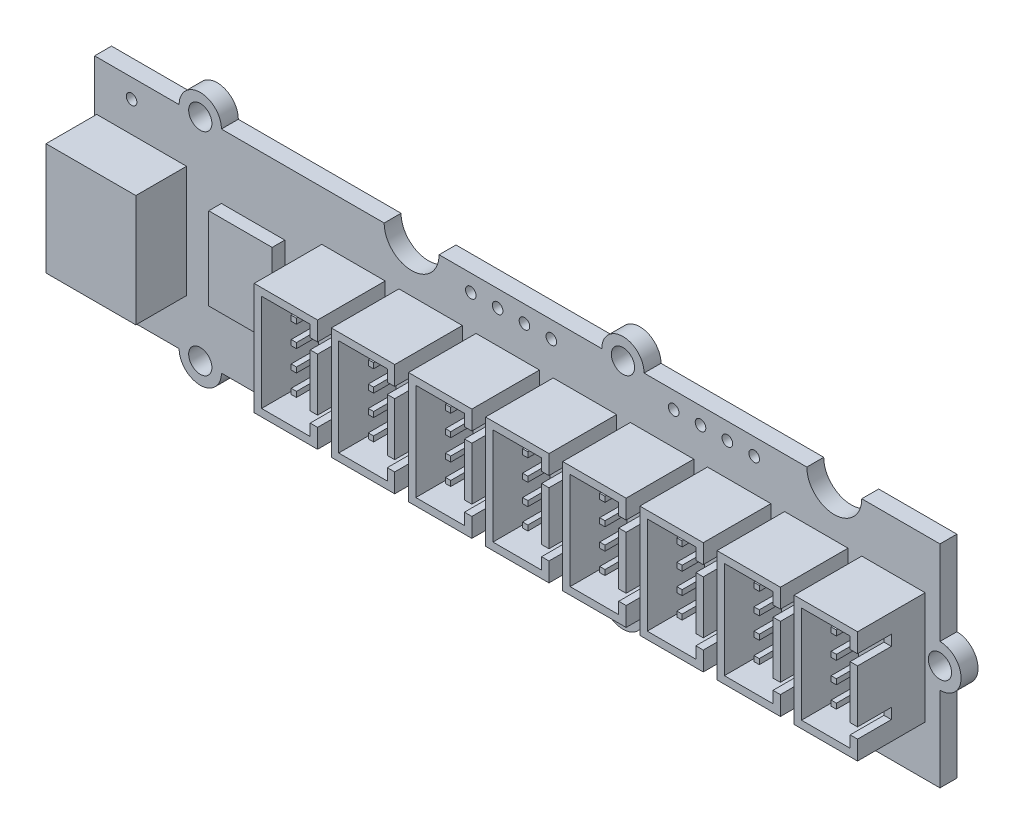
SolidWorks part; units mm, degrees
other "Grove_2"
other "Grove_1"
other "Grove_9"
other "Grove_8"
other "Grove_7"
other "Grove_6"
other "Grove_4"
other "PCB_estime"
other "Grove_3"
other "TCA9548A"
other "Grove_5"
ref_plane "Plan de face" through (0, 0, 0) normal (0, 0, 1) x (1, 0, 0)
ref_plane "Plan de dessus" through (0, 0, 0) normal (0, 1, 0) x (1, 0, 0)
ref_plane "Plan de droite" through (0, 0, 0) normal (1, 0, 0) x (0, 0, -1)
sketch "Esquisse1" plane through (0, 0, 0) normal (0, 0, 1) x (1, 0, 0)
  line L1 (0, 0) -> (80, 0)
  line L2 (0, 0) -> (0, 20)
  line L3 (0, 20) -> (80, 20)
  line L4 (80, 0) -> (80, 20)
extrude "PCB_80x20_epaisseur_ESTIMEE_1_6" add sketch "Esquisse1" along normal blind 1.6 separate body
sketch "Esquisse2" plane through (0, 0, 0) normal (0, 0, 1) x (1, 0, 0)
  circle A0 centre (10, 0) radius 2
  circle A1 centre (10, 20) radius 2
  circle A2 centre (50, 0) radius 2
  circle A3 centre (50, 20) radius 2
  circle A4 centre (80, 10) radius 2
extrude "Oreilles_fixation_ESTIMEES" add sketch "Esquisse2" along normal blind 1.6
sketch "Esquisse3" plane through (0, 0, 0) normal (0, 0, 1) x (1, 0, 0)
  circle A0 centre (10, 0) radius 1.1
  circle A1 centre (10, 20) radius 1.1
  circle A2 centre (50, 0) radius 1.1
  circle A3 centre (50, 20) radius 1.1
  circle A4 centre (80, 10) radius 1.1
  circle A5 centre (30, 0) radius 2.6
  circle A6 centre (30, 20) radius 2.6
  circle A7 centre (70, 0) radius 2.6
  circle A8 centre (70, 20) radius 2.6
  circle A9 centre (0, 10) radius 2.6
extrude "Percages_D2_2_et_encoches_ESTIMES" cut sketch "Esquisse3" against normal blind 2 from offset 1.6
sketch "Esquisse4" plane through (0, 0, 0) normal (0, 0, 1) x (1, 0, 0)
  circle A0 centre (35.6, 1.6) radius 0.5
  circle A1 centre (35.6, 18.4) radius 0.5
  circle A2 centre (38.14, 1.6) radius 0.5
  circle A3 centre (38.14, 18.4) radius 0.5
  circle A4 centre (40.68, 1.6) radius 0.5
  circle A5 centre (40.68, 18.4) radius 0.5
  circle A6 centre (43.22, 1.6) radius 0.5
  circle A7 centre (43.22, 18.4) radius 0.5
  circle A8 centre (54.8, 1.6) radius 0.5
  circle A9 centre (54.8, 18.4) radius 0.5
  circle A10 centre (57.34, 1.6) radius 0.5
  circle A11 centre (57.34, 18.4) radius 0.5
  circle A12 centre (59.88, 1.6) radius 0.5
  circle A13 centre (59.88, 18.4) radius 0.5
  circle A14 centre (62.42, 1.6) radius 0.5
  circle A15 centre (62.42, 18.4) radius 0.5
  circle A16 centre (3.5, 18.2) radius 0.5
extrude "Trous_auxiliaires_ESTIMES" cut sketch "Esquisse4" against normal blind 2 from offset 1.6
sketch "Esquisse5" plane through (0, 0, 0) normal (0, 0, 1) x (1, 0, 0)
  line L1 (21.5, 4.7) -> (27.5, 4.7)
  line L2 (21.5, 4.7) -> (21.5, 15.3)
  line L3 (21.5, 15.3) -> (27.5, 15.3)
  line L4 (27.5, 4.7) -> (27.5, 15.3)
  line L6 (28.8, 4.7) -> (34.8, 4.7)
  line L7 (28.8, 4.7) -> (28.8, 15.3)
  line L8 (28.8, 15.3) -> (34.8, 15.3)
  line L9 (34.8, 4.7) -> (34.8, 15.3)
  line L11 (36.1, 4.7) -> (42.1, 4.7)
  line L12 (36.1, 4.7) -> (36.1, 15.3)
  line L13 (36.1, 15.3) -> (42.1, 15.3)
  line L14 (42.1, 4.7) -> (42.1, 15.3)
  line L16 (43.4, 4.7) -> (49.4, 4.7)
  line L17 (43.4, 4.7) -> (43.4, 15.3)
  line L18 (43.4, 15.3) -> (49.4, 15.3)
  line L19 (49.4, 4.7) -> (49.4, 15.3)
  line L21 (50.7, 4.7) -> (56.7, 4.7)
  line L22 (50.7, 4.7) -> (50.7, 15.3)
  line L23 (50.7, 15.3) -> (56.7, 15.3)
  line L24 (56.7, 4.7) -> (56.7, 15.3)
  line L26 (58, 4.7) -> (64, 4.7)
  line L27 (58, 4.7) -> (58, 15.3)
  line L28 (58, 15.3) -> (64, 15.3)
  line L29 (64, 4.7) -> (64, 15.3)
  line L31 (65.3, 4.7) -> (71.3, 4.7)
  line L32 (65.3, 4.7) -> (65.3, 15.3)
  line L33 (65.3, 15.3) -> (71.3, 15.3)
  line L34 (71.3, 4.7) -> (71.3, 15.3)
  line L36 (72.6, 4.7) -> (78.6, 4.7)
  line L37 (72.6, 4.7) -> (72.6, 15.3)
  line L38 (72.6, 15.3) -> (78.6, 15.3)
  line L39 (78.6, 4.7) -> (78.6, 15.3)
extrude "Huit_connecteurs_sorties_ESTIMES" add sketch "Esquisse5" along normal blind 6.4 from offset 1.6 separate body
sketch "Esquisse6" plane through (0, 0, 0) normal (0, 0, 1) x (1, 0, 0)
  line L1 (22.2, 5.4) -> (26.8, 5.4)
  line L2 (22.2, 5.4) -> (22.2, 14.6)
  line L3 (22.2, 14.6) -> (26.8, 14.6)
  line L4 (26.8, 5.4) -> (26.8, 14.6)
  line L6 (29.5, 5.4) -> (34.1, 5.4)
  line L7 (29.5, 5.4) -> (29.5, 14.6)
  line L8 (29.5, 14.6) -> (34.1, 14.6)
  line L9 (34.1, 5.4) -> (34.1, 14.6)
  line L11 (36.8, 5.4) -> (41.4, 5.4)
  line L12 (36.8, 5.4) -> (36.8, 14.6)
  line L13 (36.8, 14.6) -> (41.4, 14.6)
  line L14 (41.4, 5.4) -> (41.4, 14.6)
  line L16 (44.1, 5.4) -> (48.7, 5.4)
  line L17 (44.1, 5.4) -> (44.1, 14.6)
  line L18 (44.1, 14.6) -> (48.7, 14.6)
  line L19 (48.7, 5.4) -> (48.7, 14.6)
  line L21 (51.4, 5.4) -> (56, 5.4)
  line L22 (51.4, 5.4) -> (51.4, 14.6)
  line L23 (51.4, 14.6) -> (56, 14.6)
  line L24 (56, 5.4) -> (56, 14.6)
  line L26 (58.7, 5.4) -> (63.3, 5.4)
  line L27 (58.7, 5.4) -> (58.7, 14.6)
  line L28 (58.7, 14.6) -> (63.3, 14.6)
  line L29 (63.3, 5.4) -> (63.3, 14.6)
  line L31 (66, 5.4) -> (70.6, 5.4)
  line L32 (66, 5.4) -> (66, 14.6)
  line L33 (66, 14.6) -> (70.6, 14.6)
  line L34 (70.6, 5.4) -> (70.6, 14.6)
  line L36 (73.3, 5.4) -> (77.9, 5.4)
  line L37 (73.3, 5.4) -> (73.3, 14.6)
  line L38 (73.3, 14.6) -> (77.9, 14.6)
  line L39 (77.9, 5.4) -> (77.9, 14.6)
extrude "Cavites_connecteurs" cut sketch "Esquisse6" against normal blind 5.4 from offset 8
sketch "Esquisse7" plane through (0, 0, 0) normal (0, 0, 1) x (1, 0, 0)
  line L1 (26.7, 6.5) -> (27.7, 6.5)
  line L2 (26.7, 6.5) -> (26.7, 7.5)
  line L3 (26.7, 7.5) -> (27.7, 7.5)
  line L4 (27.7, 6.5) -> (27.7, 7.5)
  line L6 (26.7, 12.5) -> (27.7, 12.5)
  line L7 (26.7, 12.5) -> (26.7, 13.5)
  line L8 (26.7, 13.5) -> (27.7, 13.5)
  line L9 (27.7, 12.5) -> (27.7, 13.5)
  line L11 (34, 6.5) -> (35, 6.5)
  line L12 (34, 6.5) -> (34, 7.5)
  line L13 (34, 7.5) -> (35, 7.5)
  line L14 (35, 6.5) -> (35, 7.5)
  line L16 (34, 12.5) -> (35, 12.5)
  line L17 (34, 12.5) -> (34, 13.5)
  line L18 (34, 13.5) -> (35, 13.5)
  line L19 (35, 12.5) -> (35, 13.5)
  line L21 (41.3, 6.5) -> (42.3, 6.5)
  line L22 (41.3, 6.5) -> (41.3, 7.5)
  line L23 (41.3, 7.5) -> (42.3, 7.5)
  line L24 (42.3, 6.5) -> (42.3, 7.5)
  line L26 (41.3, 12.5) -> (42.3, 12.5)
  line L27 (41.3, 12.5) -> (41.3, 13.5)
  line L28 (41.3, 13.5) -> (42.3, 13.5)
  line L29 (42.3, 12.5) -> (42.3, 13.5)
  line L31 (48.6, 6.5) -> (49.6, 6.5)
  line L32 (48.6, 6.5) -> (48.6, 7.5)
  line L33 (48.6, 7.5) -> (49.6, 7.5)
  line L34 (49.6, 6.5) -> (49.6, 7.5)
  line L36 (48.6, 12.5) -> (49.6, 12.5)
  line L37 (48.6, 12.5) -> (48.6, 13.5)
  line L38 (48.6, 13.5) -> (49.6, 13.5)
  line L39 (49.6, 12.5) -> (49.6, 13.5)
  line L41 (55.9, 6.5) -> (56.9, 6.5)
  line L42 (55.9, 6.5) -> (55.9, 7.5)
  line L43 (55.9, 7.5) -> (56.9, 7.5)
  line L44 (56.9, 6.5) -> (56.9, 7.5)
  line L46 (55.9, 12.5) -> (56.9, 12.5)
  line L47 (55.9, 12.5) -> (55.9, 13.5)
  line L48 (55.9, 13.5) -> (56.9, 13.5)
  line L49 (56.9, 12.5) -> (56.9, 13.5)
  line L51 (63.2, 6.5) -> (64.2, 6.5)
  line L52 (63.2, 6.5) -> (63.2, 7.5)
  line L53 (63.2, 7.5) -> (64.2, 7.5)
  line L54 (64.2, 6.5) -> (64.2, 7.5)
  line L56 (63.2, 12.5) -> (64.2, 12.5)
  line L57 (63.2, 12.5) -> (63.2, 13.5)
  line L58 (63.2, 13.5) -> (64.2, 13.5)
  line L59 (64.2, 12.5) -> (64.2, 13.5)
  line L61 (70.5, 6.5) -> (71.5, 6.5)
  line L62 (70.5, 6.5) -> (70.5, 7.5)
  line L63 (70.5, 7.5) -> (71.5, 7.5)
  line L64 (71.5, 6.5) -> (71.5, 7.5)
  line L66 (70.5, 12.5) -> (71.5, 12.5)
  line L67 (70.5, 12.5) -> (70.5, 13.5)
  line L68 (70.5, 13.5) -> (71.5, 13.5)
  line L69 (71.5, 12.5) -> (71.5, 13.5)
  line L71 (77.8, 6.5) -> (78.8, 6.5)
  line L72 (77.8, 6.5) -> (77.8, 7.5)
  line L73 (77.8, 7.5) -> (78.8, 7.5)
  line L74 (78.8, 6.5) -> (78.8, 7.5)
  line L76 (77.8, 12.5) -> (78.8, 12.5)
  line L77 (77.8, 12.5) -> (77.8, 13.5)
  line L78 (77.8, 13.5) -> (78.8, 13.5)
  line L79 (78.8, 12.5) -> (78.8, 13.5)
extrude "Encoches_detrompage_simplifiees" cut sketch "Esquisse7" against normal blind 3.2 from offset 8
sketch "Esquisse8" plane through (0, 0, 0) normal (0, 0, 1) x (1, 0, 0)
  line L1 (0.2, 4.7) -> (8.7, 4.7)
  line L2 (0.2, 4.7) -> (0.2, 15.3)
  line L3 (0.2, 15.3) -> (8.7, 15.3)
  line L4 (8.7, 4.7) -> (8.7, 15.3)
extrude "Connecteur_entree_coude_ESTIME" add sketch "Esquisse8" along normal blind 4.8 from offset 1.6 separate body
sketch "Esquisse9" plane through (0, 0, 0) normal (0, 0, 1) x (1, 0, 0)
  line L1 (-0.5, 5.4) -> (6.1, 5.4)
  line L2 (-0.5, 5.4) -> (-0.5, 14.6)
  line L3 (-0.5, 14.6) -> (6.1, 14.6)
  line L4 (6.1, 5.4) -> (6.1, 14.6)
extrude "Ouverture_entree_simplifiee" cut sketch "Esquisse9" against normal blind 3.1 from offset 5.7
sketch "Esquisse10" plane through (0, 0, 0) normal (0, 0, 1) x (1, 0, 0)
  line L1 (12, 6.1) -> (18, 6.1)
  line L2 (12, 6.1) -> (12, 13.9)
  line L3 (12, 13.9) -> (18, 13.9)
  line L4 (18, 6.1) -> (18, 13.9)
extrude "TCA9548A_boitier_simplifie" add sketch "Esquisse10" along normal blind 1.2 from offset 1.6 separate body
sketch "Esquisse11" plane through (0, 0, 0) normal (0, 0, 1) x (1, 0, 0)
  line L1 (23.8, 6.75) -> (24.3, 6.75)
  line L2 (23.8, 6.75) -> (23.8, 7.25)
  line L3 (23.8, 7.25) -> (24.3, 7.25)
  line L4 (24.3, 6.75) -> (24.3, 7.25)
  line L6 (23.8, 8.75) -> (24.3, 8.75)
  line L7 (23.8, 8.75) -> (23.8, 9.25)
  line L8 (23.8, 9.25) -> (24.3, 9.25)
  line L9 (24.3, 8.75) -> (24.3, 9.25)
  line L11 (23.8, 10.75) -> (24.3, 10.75)
  line L12 (23.8, 10.75) -> (23.8, 11.25)
  line L13 (23.8, 11.25) -> (24.3, 11.25)
  line L14 (24.3, 10.75) -> (24.3, 11.25)
  line L16 (23.8, 12.75) -> (24.3, 12.75)
  line L17 (23.8, 12.75) -> (23.8, 13.25)
  line L18 (23.8, 13.25) -> (24.3, 13.25)
  line L19 (24.3, 12.75) -> (24.3, 13.25)
  line L21 (31.1, 6.75) -> (31.6, 6.75)
  line L22 (31.1, 6.75) -> (31.1, 7.25)
  line L23 (31.1, 7.25) -> (31.6, 7.25)
  line L24 (31.6, 6.75) -> (31.6, 7.25)
  line L26 (31.1, 8.75) -> (31.6, 8.75)
  line L27 (31.1, 8.75) -> (31.1, 9.25)
  line L28 (31.1, 9.25) -> (31.6, 9.25)
  line L29 (31.6, 8.75) -> (31.6, 9.25)
  line L31 (31.1, 10.75) -> (31.6, 10.75)
  line L32 (31.1, 10.75) -> (31.1, 11.25)
  line L33 (31.1, 11.25) -> (31.6, 11.25)
  line L34 (31.6, 10.75) -> (31.6, 11.25)
  line L36 (31.1, 12.75) -> (31.6, 12.75)
  line L37 (31.1, 12.75) -> (31.1, 13.25)
  line L38 (31.1, 13.25) -> (31.6, 13.25)
  line L39 (31.6, 12.75) -> (31.6, 13.25)
  line L41 (38.4, 6.75) -> (38.9, 6.75)
  line L42 (38.4, 6.75) -> (38.4, 7.25)
  line L43 (38.4, 7.25) -> (38.9, 7.25)
  line L44 (38.9, 6.75) -> (38.9, 7.25)
  line L46 (38.4, 8.75) -> (38.9, 8.75)
  line L47 (38.4, 8.75) -> (38.4, 9.25)
  line L48 (38.4, 9.25) -> (38.9, 9.25)
  line L49 (38.9, 8.75) -> (38.9, 9.25)
  line L51 (38.4, 10.75) -> (38.9, 10.75)
  line L52 (38.4, 10.75) -> (38.4, 11.25)
  line L53 (38.4, 11.25) -> (38.9, 11.25)
  line L54 (38.9, 10.75) -> (38.9, 11.25)
  line L56 (38.4, 12.75) -> (38.9, 12.75)
  line L57 (38.4, 12.75) -> (38.4, 13.25)
  line L58 (38.4, 13.25) -> (38.9, 13.25)
  line L59 (38.9, 12.75) -> (38.9, 13.25)
  line L61 (45.7, 6.75) -> (46.2, 6.75)
  line L62 (45.7, 6.75) -> (45.7, 7.25)
  line L63 (45.7, 7.25) -> (46.2, 7.25)
  line L64 (46.2, 6.75) -> (46.2, 7.25)
  line L66 (45.7, 8.75) -> (46.2, 8.75)
  line L67 (45.7, 8.75) -> (45.7, 9.25)
  line L68 (45.7, 9.25) -> (46.2, 9.25)
  line L69 (46.2, 8.75) -> (46.2, 9.25)
  line L71 (45.7, 10.75) -> (46.2, 10.75)
  line L72 (45.7, 10.75) -> (45.7, 11.25)
  line L73 (45.7, 11.25) -> (46.2, 11.25)
  line L74 (46.2, 10.75) -> (46.2, 11.25)
  line L76 (45.7, 12.75) -> (46.2, 12.75)
  line L77 (45.7, 12.75) -> (45.7, 13.25)
  line L78 (45.7, 13.25) -> (46.2, 13.25)
  line L79 (46.2, 12.75) -> (46.2, 13.25)
  line L81 (53, 6.75) -> (53.5, 6.75)
  line L82 (53, 6.75) -> (53, 7.25)
  line L83 (53, 7.25) -> (53.5, 7.25)
  line L84 (53.5, 6.75) -> (53.5, 7.25)
  line L86 (53, 8.75) -> (53.5, 8.75)
  line L87 (53, 8.75) -> (53, 9.25)
  line L88 (53, 9.25) -> (53.5, 9.25)
  line L89 (53.5, 8.75) -> (53.5, 9.25)
  line L91 (53, 10.75) -> (53.5, 10.75)
  line L92 (53, 10.75) -> (53, 11.25)
  line L93 (53, 11.25) -> (53.5, 11.25)
  line L94 (53.5, 10.75) -> (53.5, 11.25)
  line L96 (53, 12.75) -> (53.5, 12.75)
  line L97 (53, 12.75) -> (53, 13.25)
  line L98 (53, 13.25) -> (53.5, 13.25)
  line L99 (53.5, 12.75) -> (53.5, 13.25)
  line L101 (60.3, 6.75) -> (60.8, 6.75)
  line L102 (60.3, 6.75) -> (60.3, 7.25)
  line L103 (60.3, 7.25) -> (60.8, 7.25)
  line L104 (60.8, 6.75) -> (60.8, 7.25)
  line L106 (60.3, 8.75) -> (60.8, 8.75)
  line L107 (60.3, 8.75) -> (60.3, 9.25)
  line L108 (60.3, 9.25) -> (60.8, 9.25)
  line L109 (60.8, 8.75) -> (60.8, 9.25)
  line L111 (60.3, 10.75) -> (60.8, 10.75)
  line L112 (60.3, 10.75) -> (60.3, 11.25)
  line L113 (60.3, 11.25) -> (60.8, 11.25)
  line L114 (60.8, 10.75) -> (60.8, 11.25)
  line L116 (60.3, 12.75) -> (60.8, 12.75)
  line L117 (60.3, 12.75) -> (60.3, 13.25)
  line L118 (60.3, 13.25) -> (60.8, 13.25)
  line L119 (60.8, 12.75) -> (60.8, 13.25)
  line L121 (67.6, 6.75) -> (68.1, 6.75)
  line L122 (67.6, 6.75) -> (67.6, 7.25)
  line L123 (67.6, 7.25) -> (68.1, 7.25)
  line L124 (68.1, 6.75) -> (68.1, 7.25)
  line L126 (67.6, 8.75) -> (68.1, 8.75)
  line L127 (67.6, 8.75) -> (67.6, 9.25)
  line L128 (67.6, 9.25) -> (68.1, 9.25)
  line L129 (68.1, 8.75) -> (68.1, 9.25)
  line L131 (67.6, 10.75) -> (68.1, 10.75)
  line L132 (67.6, 10.75) -> (67.6, 11.25)
  line L133 (67.6, 11.25) -> (68.1, 11.25)
  line L134 (68.1, 10.75) -> (68.1, 11.25)
  line L136 (67.6, 12.75) -> (68.1, 12.75)
  line L137 (67.6, 12.75) -> (67.6, 13.25)
  line L138 (67.6, 13.25) -> (68.1, 13.25)
  line L139 (68.1, 12.75) -> (68.1, 13.25)
  line L141 (74.9, 6.75) -> (75.4, 6.75)
  line L142 (74.9, 6.75) -> (74.9, 7.25)
  line L143 (74.9, 7.25) -> (75.4, 7.25)
  line L144 (75.4, 6.75) -> (75.4, 7.25)
  line L146 (74.9, 8.75) -> (75.4, 8.75)
  line L147 (74.9, 8.75) -> (74.9, 9.25)
  line L148 (74.9, 9.25) -> (75.4, 9.25)
  line L149 (75.4, 8.75) -> (75.4, 9.25)
  line L151 (74.9, 10.75) -> (75.4, 10.75)
  line L152 (74.9, 10.75) -> (74.9, 11.25)
  line L153 (74.9, 11.25) -> (75.4, 11.25)
  line L154 (75.4, 10.75) -> (75.4, 11.25)
  line L156 (74.9, 12.75) -> (75.4, 12.75)
  line L157 (74.9, 12.75) -> (74.9, 13.25)
  line L158 (74.9, 13.25) -> (75.4, 13.25)
  line L159 (75.4, 12.75) -> (75.4, 13.25)
extrude "Contacts_sorties_pas_2mm" add sketch "Esquisse11" along normal blind 4.2 from offset 2.6 separate body
sketch "Esquisse12" plane through (0, 0, 0) normal (0, 0, 1) x (1, 0, 0)
  line L1 (1.5, 6.75) -> (6.5, 6.75)
  line L2 (1.5, 6.75) -> (1.5, 7.25)
  line L3 (1.5, 7.25) -> (6.5, 7.25)
  line L4 (6.5, 6.75) -> (6.5, 7.25)
  line L6 (1.5, 8.75) -> (6.5, 8.75)
  line L7 (1.5, 8.75) -> (1.5, 9.25)
  line L8 (1.5, 9.25) -> (6.5, 9.25)
  line L9 (6.5, 8.75) -> (6.5, 9.25)
  line L11 (1.5, 10.75) -> (6.5, 10.75)
  line L12 (1.5, 10.75) -> (1.5, 11.25)
  line L13 (1.5, 11.25) -> (6.5, 11.25)
  line L14 (6.5, 10.75) -> (6.5, 11.25)
  line L16 (1.5, 12.75) -> (6.5, 12.75)
  line L17 (1.5, 12.75) -> (1.5, 13.25)
  line L18 (1.5, 13.25) -> (6.5, 13.25)
  line L19 (6.5, 12.75) -> (6.5, 13.25)
extrude "Contacts_entree" add sketch "Esquisse12" along normal blind 0.5 from offset 3 separate body
